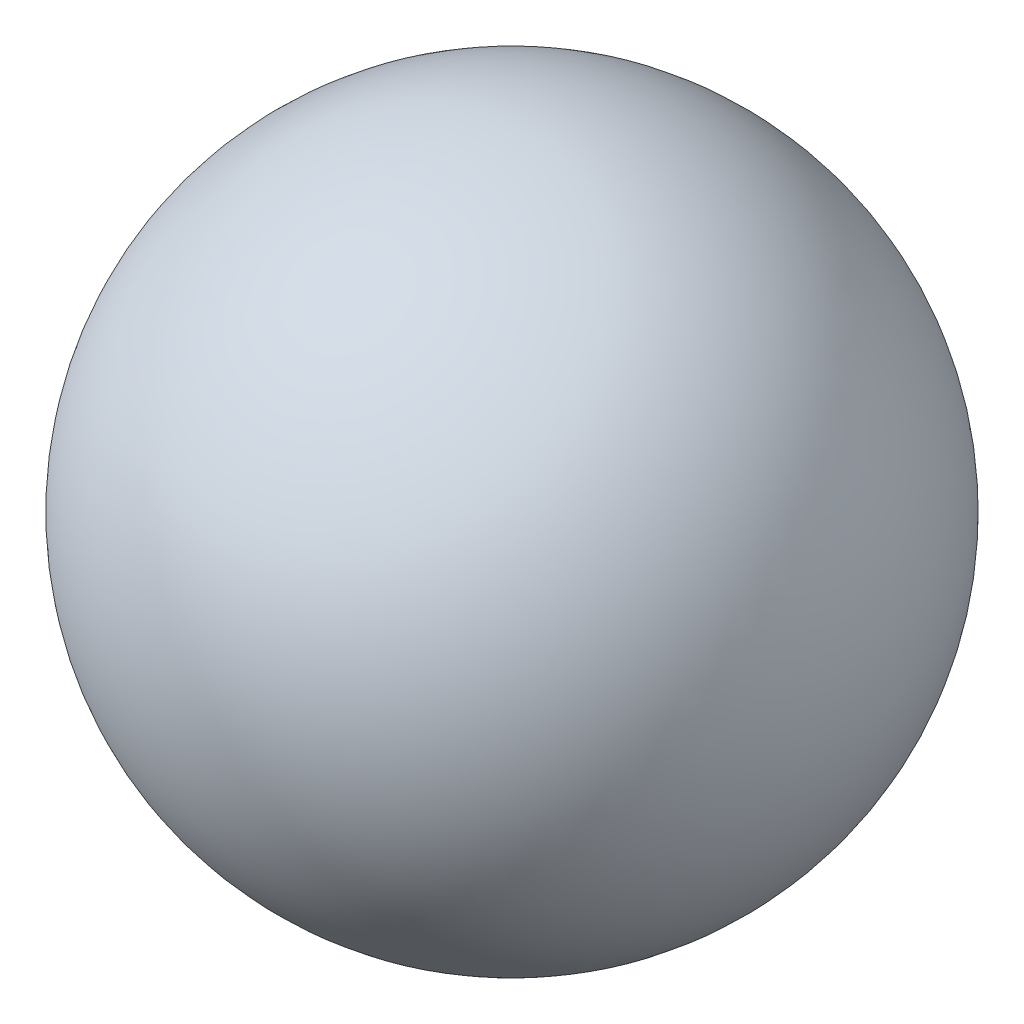
SolidWorks part; units mm, degrees
ref_plane "前视基准面" through (0, 0, 0) normal (0, 0, 1) x (1, 0, 0)
ref_plane "上视基准面" through (0, 0, 0) normal (0, 1, 0) x (1, 0, 0)
ref_plane "右视基准面" through (0, 0, 0) normal (1, 0, 0) x (0, 0, -1)
other "Configuration Table"
sketch "草图1" plane through (0, 0, 0) normal (0, 0, 1) x (1, 0, 0)
  line L0 (0, -1000) -> (0, 49000) construction
  line L1 (0, 20) -> (0, 18)
  line L2 (0, -18) -> (0, -20)
  arc A2 (0, -20) -> (0, 20) centre (0, 0) ccw
  arc A3 (0, -18) -> (0, 18) centre (0, 0) ccw
  dimension "D1" = 40
  dimension "D2" = 36
revolve "旋转4" add sketch "草图1" angle 360 about L0
